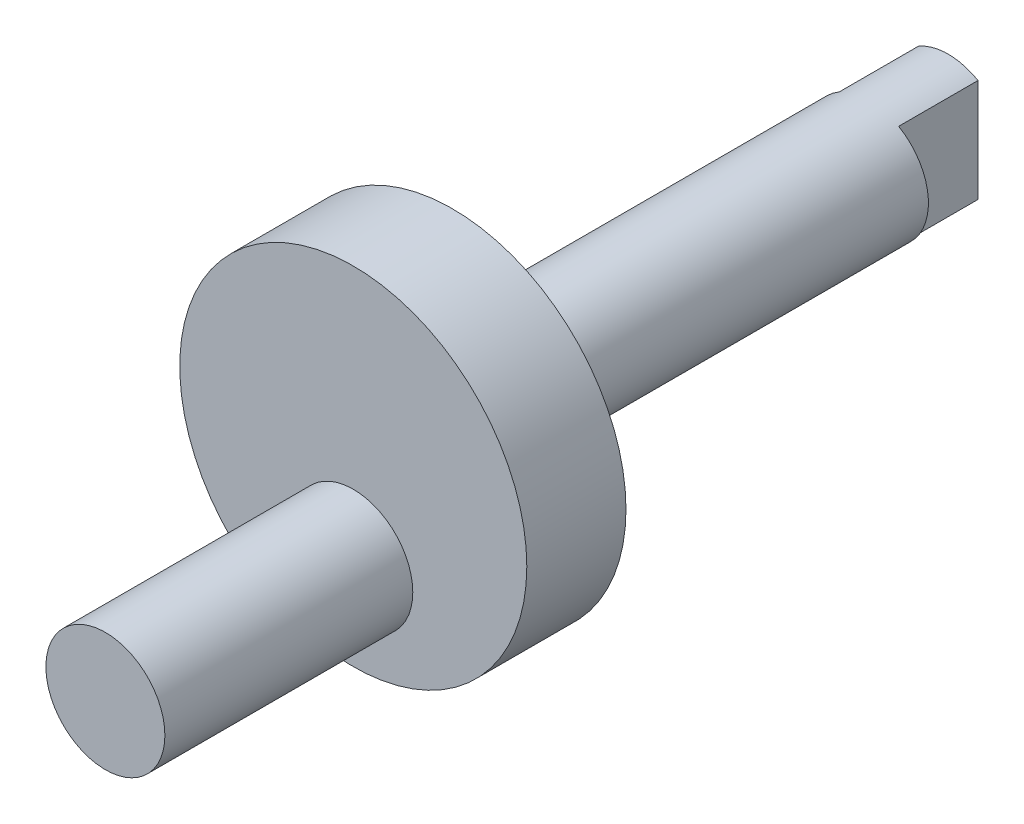
SolidWorks part; units mm, degrees
ref_plane "Front Plane" through (0, 0, 0) normal (0, 0, 1) x (1, 0, 0)
ref_plane "Top Plane" through (0, 0, 0) normal (0, 1, 0) x (1, 0, 0)
ref_plane "Right Plane" through (0, 0, 0) normal (1, 0, 0) x (0, 0, -1)
sketch "Sketch1" plane through (0, 0, 0) normal (0, 0, 1) x (1, 0, 0)
  circle A0 centre (0, 0) radius 6
  dimension "D1" = 12
extrude "Boss-Extrude1" add sketch "Sketch1" along normal blind 50
sketch "Sketch2" plane through (0, 0, 50) normal (0, 0, 1) x (1, 0, 0)
  circle A0 centre (0, 0) radius 17.5
  dimension "D1" = 35
extrude "Boss-Extrude2" add sketch "Sketch2" along normal blind 10
sketch "Sketch3" plane through (0, 0, 60) normal (0, 0, 1) x (1, 0, 0)
  circle A0 centre (0, -8) radius 6
  dimension "D1" = 12
  dimension "D2" = 8
extrude "Boss-Extrude3" add sketch "Sketch3" along normal blind 25
sketch "Sketch4" plane through (0, 0, 0) normal (0, 0, -1) x (-1, 0, 0)
  line L1 (3, -6) -> (-3, -6)
  line L2 (3, -6) -> (3, 6)
  line L3 (3, 6) -> (-3, 6)
  line L4 (-3, -6) -> (-3, 6)
  line L5 (3, -6) -> (-3, 6) construction
  line L6 (3, 6) -> (-3, -6) construction
  point P0 (0, 0)
  dimension "D1" = 6
  dimension "D2" = 12
extrude "Cut-Extrude2" cut sketch "Sketch4" against normal blind 8 flip side to cut contours L2 L1 L4 L3
